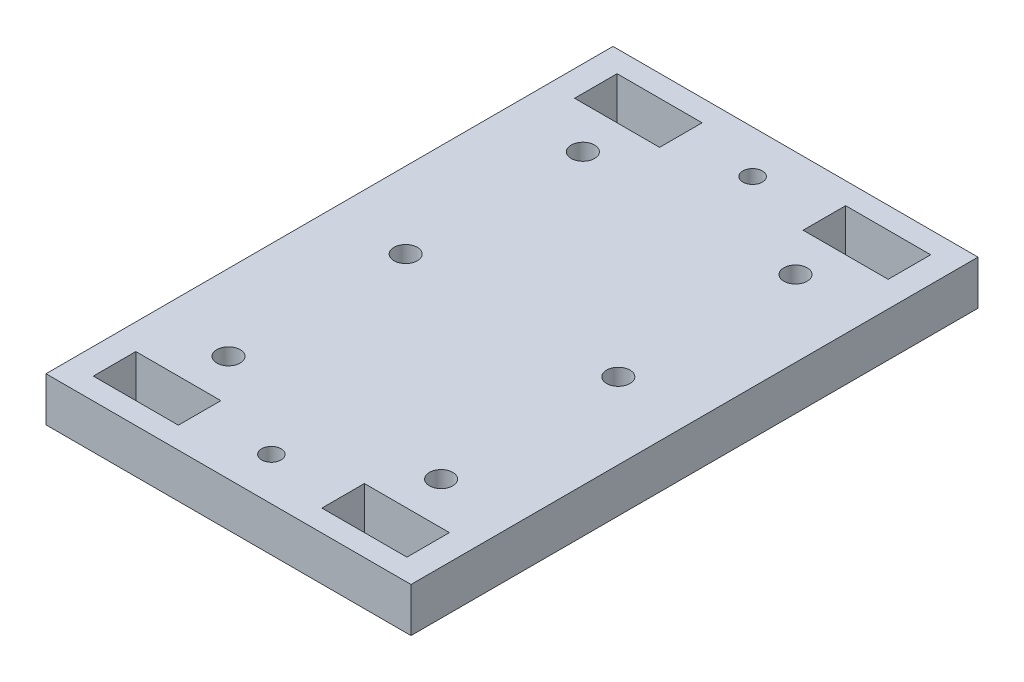
SolidWorks part; units mm, degrees
material "6061 Alloy"
ref_plane "Front Plane" through (0, 0, 0) normal (0, 0, 1) x (1, 0, 0)
ref_plane "Top Plane" through (0, 0, 0) normal (0, 1, 0) x (1, 0, 0)
ref_plane "Right Plane" through (0, 0, 0) normal (1, 0, 0) x (0, 0, -1)
sketch "Sketch1" plane through (0, 0, 0) normal (0, 1, 0) x (1, 0, 0)
  line L0 (10.75, 15) -> (40.75, 65) construction
  line L1 (0, 0) -> (51.5, 0)
  line L2 (0, 0) -> (0, 80)
  line L3 (0, 80) -> (51.5, 80)
  line L4 (51.5, 0) -> (51.5, 80)
  line L5 (10.75, 65) -> (40.75, 15) construction
  line L6 (10.75, 15) -> (40.75, 15) construction
  line L7 (10.75, 15) -> (10.75, 40) construction
  line L8 (74.8353, 40) -> (-18.4365, 40) construction
  line L9 (35.875, 76.95) -> (47.875, 76.95)
  line L10 (35.875, 76.95) -> (35.875, 70.95)
  line L11 (35.875, 70.95) -> (47.875, 70.95)
  line L12 (47.875, 76.95) -> (47.875, 70.95)
  line L13 (35.875, 76.95) -> (47.875, 70.95) construction
  line L14 (35.875, 70.95) -> (47.875, 76.95) construction
  line L15 (25.75, 90.0909) -> (25.75, -32.1217) construction
  line L16 (35.875, 3.05) -> (47.875, 9.05) construction
  line L17 (35.875, 9.05) -> (47.875, 3.05) construction
  line L18 (35.875, 3.05) -> (35.875, 9.05)
  line L19 (35.875, 3.05) -> (47.875, 3.05)
  line L20 (47.875, 3.05) -> (47.875, 9.05)
  line L21 (35.875, 9.05) -> (47.875, 9.05)
  line L22 (15.625, 76.95) -> (3.625, 70.95) construction
  line L23 (15.625, 70.95) -> (3.625, 76.95) construction
  line L24 (15.625, 3.05) -> (3.625, 9.05) construction
  line L25 (15.625, 3.05) -> (15.625, 9.05)
  line L26 (15.625, 3.05) -> (3.625, 3.05)
  line L27 (15.625, 9.05) -> (3.625, 9.05)
  line L28 (3.625, 3.05) -> (3.625, 9.05)
  line L29 (15.625, 9.05) -> (3.625, 3.05) construction
  line L30 (15.625, 76.95) -> (15.625, 70.95)
  line L31 (15.625, 76.95) -> (3.625, 76.95)
  line L32 (3.625, 76.95) -> (3.625, 70.95)
  line L33 (15.625, 70.95) -> (3.625, 70.95)
  circle A0 centre (10.75, 15) radius 1.65
  circle A1 centre (40.75, 15) radius 1.65
  circle A2 centre (25.75, 73.95) radius 1.375
  circle A3 centre (40.75, 40) radius 1.65
  circle A4 centre (25.75, 6.05) radius 1.375
  circle A5 centre (40.75, 65) radius 1.65
  circle A9 centre (10.75, 40) radius 1.65
  circle A10 centre (10.75, 65) radius 1.65
  point P7 (25.75, 40)
  point P8 (51.5, 40)
  point P9 (25.75, 0)
  point P13 (41.875, 73.95)
  point P32 (41.875, 6.05)
  point P45 (9.625, 6.05)
  point P46 (9.625, 73.95)
  dimension "D3" = 3.3
  dimension "D13" = 2.75
  dimension "D1" = 80
  dimension "D2" = 51.5
  dimension "D6" = 30
  dimension "D7" = 25
  dimension "D8" = 90
  dimension "D9" = 6
  dimension "D10" = 12
  dimension "D11" = 67.9
  dimension "D12" = 32.25
  dimension "D4" = 2
  dimension "D5" = 3
extrude "Boss-Extrude1" add sketch "Sketch1" along normal blind 6.25
